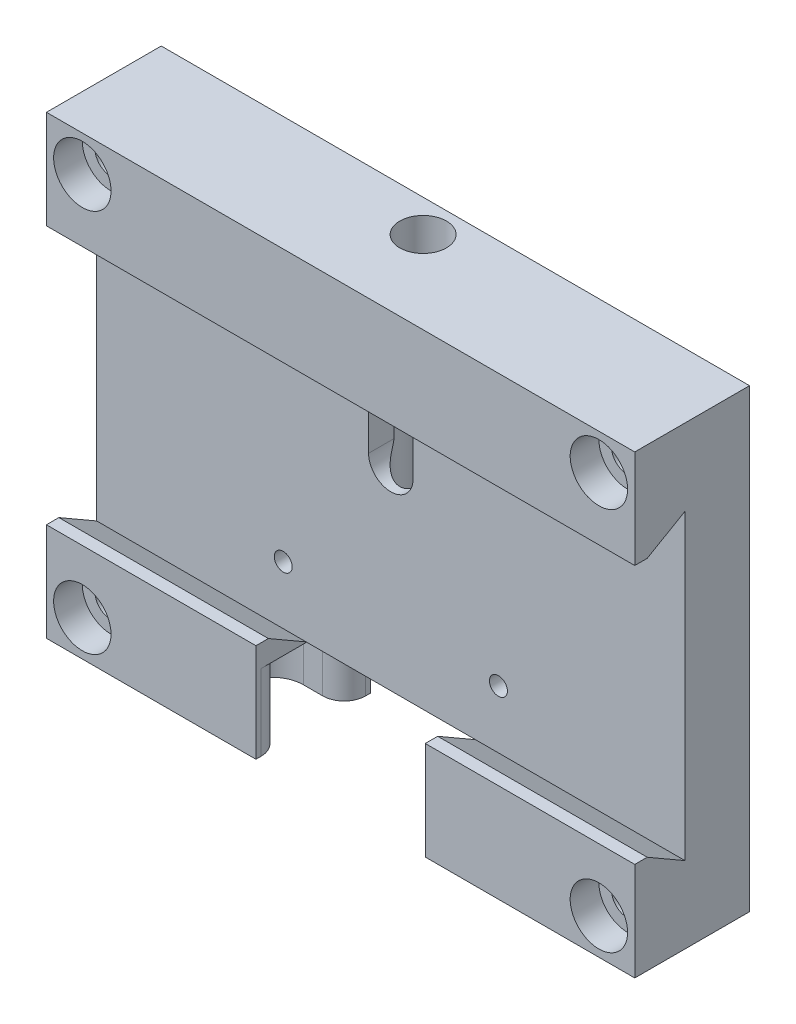
SolidWorks part; units mm, degrees
material "Сплав 2024"
ref_plane "Спереди" through (0, 0, 0) normal (0, 0, 1) x (1, 0, 0)
ref_plane "Сверху" through (0, 0, 0) normal (0, 1, 0) x (1, 0, 0)
ref_plane "Справа" through (0, 0, 0) normal (1, 0, 0) x (0, 0, -1)
sketch "Эскиз1" plane through (0, 0, 0) normal (0, 0, 1) x (1, 0, 0)
  line L1 (0, 0) -> (82, 0)
  line L2 (0, 0) -> (0, -63.5)
  line L3 (0, -63.5) -> (82, -63.5)
  line L4 (82, 0) -> (82, -63.5)
  dimension "D1" = 63.5
  dimension "D2" = 82
extrude "Бобышка-Вытянуть1" add sketch "Эскиз1" along normal blind 16
sketch "Эскиз2" plane through (0, 0, 0) normal (-1, 0, 0) x (0, 0, 1)
  line L0 (0, -31.75) -> (12.8711, -31.75) construction
  line L1 (0, 0) -> (0, -63.5) construction
  line L3 (16, 0) -> (16, -63.5) construction
  line L4 (9, -10.67) -> (16, -14.7115)
  line L5 (9, -10.67) -> (9, -52.83)
  line L6 (9, -52.83) -> (16, -48.7885)
  line L7 (16, -14.7115) -> (16, -48.7885)
  line L8 (9, -10.67) -> (16, -48.7885) construction
  line L9 (9, -52.83) -> (16, -14.7115) construction
  dimension "D1" = 42.16
  dimension "D2" = 60
  dimension "D3" = 60
  dimension "D4" = 7
extrude "Вырез-Вытянуть1" cut sketch "Эскиз2" against normal through all
ref_plane "Плоскость1" through (0, 0, 4) normal (0, 0, 1) x (1, 0, 0)
sketch "Эскиз11" plane through (0, 0, 0) normal (0, 0, -1) x (-1, 0, 0)
  line L0 (-82, -5) -> (0, -5) construction
  line L1 (-82, -63.5) -> (-82, 0) construction
  line L2 (0, 0) -> (0, -63.5) construction
  line L3 (-82, -58.5) -> (0, -58.5) construction
  line L4 (-82, 0) -> (0, 0) construction
  line L5 (0, -63.5) -> (-82, -63.5) construction
  line L8 (-82, -31.75) -> (0, -31.75) construction
  line L9 (-41, 0) -> (-41, -63.5) construction
  line L10 (-77, 0) -> (-77, -63.5) construction
  line L11 (-63.5, -11.75) -> (-18.5, -11.75) construction
  line L12 (-63.5, -11.75) -> (-63.5, -51.75) construction
  line L13 (-63.5, -51.75) -> (-18.5, -51.75) construction
  line L14 (-18.5, -11.75) -> (-18.5, -51.75) construction
  line L15 (-63.5, -11.75) -> (-18.5, -51.75) construction
  line L16 (-63.5, -51.75) -> (-18.5, -11.75) construction
  line L17 (-82, 0) -> (0, 0) construction
  line L18 (-82, -10.67) -> (-82, -52.83) construction
  line L19 (-5, 0) -> (-5, -63.5) construction
  line L20 (0, -10.67) -> (0, -52.83) construction
  line L21 (0, -63.5) -> (-82, -63.5) construction
  point P20 (-41, -31.75)
  dimension "D1" = 5
  dimension "D2" = 5
  dimension "D3" = 5
  dimension "D4" = 5
  dimension "D5" = 45
  dimension "D6" = 40
sketch "Эскиз15" plane through (0, 0, 16) normal (0, 0, 1) x (1, 0, 0)
  line L0 (41, 0) -> (41, -63.5) construction
  line L1 (82, 0) -> (0, 0) construction
  line L2 (0, -63.5) -> (82, -63.5) construction
  line L3 (82, -48.7885) -> (0, -48.7885) construction
  line L4 (29.2, -48.7885) -> (52.8, -48.7885)
  line L5 (29.2, -48.7885) -> (29.2, -63.5)
  line L6 (29.2, -63.5) -> (52.8, -63.5)
  line L7 (52.8, -48.7885) -> (52.8, -63.5)
  line L8 (29.2, -48.7885) -> (52.8, -63.5) construction
  line L9 (29.2, -63.5) -> (52.8, -48.7885) construction
  point P6 (41, -56.1443)
  dimension "D1" = 23.6
extrude "Вырез-Вытянуть4" cut sketch "Эскиз15" against normal up to surface (7 mm away) up to face at (41, -31.75, 9)
sketch "Эскиз16" plane through (0, 0, 9) normal (0, 0, 1) x (1, 0, 0)
  line L0 (41, 0) -> (41, -63.5) construction
  line L1 (29.2, -52.83) -> (52.8, -52.83)
  line L2 (29.2, -52.83) -> (29.2, -63.5)
  line L3 (29.2, -63.5) -> (52.8, -63.5)
  line L4 (52.8, -52.83) -> (52.8, -63.5)
  line L5 (29.2, -52.83) -> (52.8, -63.5) construction
  line L6 (29.2, -63.5) -> (52.8, -52.83) construction
  line L7 (29.2, -63.5) -> (52.8, -63.5) construction
  line L8 (82, -52.83) -> (52.8, -52.83) construction
  line L9 (52.8, -63.5) -> (52.8, -52.83) construction
  point P0 (41, -58.165)
extrude "Вырез-Вытянуть5" cut sketch "Эскиз16" against normal up to surface (9 mm away) up to face at (41, -31.75, 0)
sketch "Эскиз17" plane through (0, -52.83, 0) normal (0, -1, 0) x (1, 0, 0)
  line L0 (35.125, 5) -> (60.125, 5) construction
  line L3 (41, 9) -> (41, 0) construction
  line L4 (82, 9) -> (0, 9) construction
  line L5 (29.2, 0) -> (52.8, 0) construction
  circle A0 centre (33.5, 5) radius 2.5
  circle A1 centre (48.5, 5) radius 2.5
  dimension "D1" = 5
  dimension "D2" = 7.5
  dimension "D3" = 5
extrude "Вырез-Вытянуть6" cut sketch "Эскиз17" against normal blind 8
hole_wizard "Отверстие обработанное метчиком M4x0.72" positions "Эскиз19" profile "Эскиз18" tap size "M4x0.7" standard "Ansi Metric"
sketch "Эскиз19" plane through (0, -52.83, 0) normal (0, -1, 0) x (-1, 0, 0)
  line L0 (-41, -9) -> (-41, 0) construction
  line L1 (-35.125, -5) -> (-60.125, -5) construction
  point P0 (-41, -5)
sketch "Эскиз18" plane through (41, -52.83, 5) normal (1, 0, 0) x (0, 0, -1)
  line L0 (0, 0) -> (0, 10.9914)
  line L1 (0, 10.9914) -> (1.65, 10)
  line L2 (1.65, 10) -> (1.65, 0)
  line L5 (1.65, 0) -> (0, 0)
  line L10 (0, 10.9914) -> (-1.65, 10) construction
  line L11 (0, -6.35) -> (0, 107.95) construction
  dimension "Диаметр сверла" = 3.3
  dimension "Глубина сверла" = 10
  dimension "Угол заточки сверла" = 118
cosmetic thread "Отверстие резьбы9" parameters "D1"=8, "D2"=4
sketch "Эскиз25" plane through (0, 0, 9) normal (0, 0, 1) x (1, 0, 0)
  line L0 (41, 0) -> (41, -52.83) construction
  line L1 (82, 0) -> (0, 0) construction
  line L2 (52.8, -52.83) -> (29.2, -52.83) construction
  line L3 (41, -18.7115) -> (41, -25.7115) construction
  line L4 (44.1, -18.7115) -> (44.1, -25.7115)
  line L5 (37.9, -18.7115) -> (37.9, -25.7115)
  line L6 (82, -14.7115) -> (0, -14.7115) construction
  arc A0 (44.1, -18.7115) -> (37.9, -18.7115) centre (41, -18.7115) ccw
  arc A1 (37.9, -25.7115) -> (44.1, -25.7115) centre (41, -25.7115) ccw
  point P8 (41, -22.2115)
  dimension "D1" = 3.1
  dimension "D2" = 4
  dimension "D3" = 7
extrude "Вырез-Вытянуть7" cut sketch "Эскиз25" against normal blind 4
sketch "Эскиз26" plane through (0, 0, 0) normal (0, 1, 0) x (1, 0, 0)
  line L0 (0, -9) -> (82, -9) construction
  line L1 (0, -16) -> (0, 0) construction
  line L2 (82, -16) -> (82, 0) construction
  line L4 (82, 0) -> (0, 0) construction
  line L5 (41, 0) -> (41, -16) construction
  line L6 (82, -16) -> (0, -16) construction
  circle A0 centre (41, -4.5) radius 3.25
  dimension "D2" = 6.5
  dimension "D1" = 9
  dimension "D3" = 4.5
extrude "Вырез-Вытянуть8" cut sketch "Эскиз26" against normal blind 38
hole_wizard "Цековка для винта с внутренним шестигранником M41" positions "Эскиз29" profile "Эскиз28" counterbore size "M4" standard "Ansi Metric" end condition through all
sketch "Эскиз29" plane through (30.7592, 26.7934, 16) normal (0, 0, -1) x (-1, 0, 0)
  line L0 (-51.2408, -31.7934) -> (30.7592, -31.7934) construction
  line L1 (-46.2408, -26.7934) -> (-46.2408, -90.2934) construction
  line L2 (-51.2408, -85.2934) -> (30.7592, -85.2934) construction
  line L3 (25.7592, -26.7934) -> (25.7592, -90.2934) construction
  point P0 (-46.2408, -31.7934)
  point P6 (-46.2408, -85.2934)
  point P10 (25.7592, -85.2934)
  point P14 (25.7592, -31.7934)
sketch "Эскиз28" plane through (77, -5, 16) normal (1, 0, 0) x (0, -1, 0)
  line L0 (0, 0) -> (0, 16)
  line L1 (0, 16) -> (2.25, 16)
  line L3 (2.25, 16) -> (2.25, 4)
  line L4 (2.25, 4) -> (4, 4)
  line L5 (4, 4) -> (4, 0)
  line L7 (4, 0) -> (0, 0)
  line L11 (0, -6.35) -> (0, 107.95) construction
  dimension "Диаметр сквозного отверстия" = 4.5
  dimension "Глубина сквозного отверстия" = 16
  dimension "Диаметр цековки" = 8
  dimension "Глубина цековки" = 4
chamfer "Фаска2" distance 1 angle 90 3 edges at (67.4, -48.7885, 16) (14.6, -48.7885, 16) (41, -14.7115, 16)
sketch "Эскиз32" plane through (0, -63.5, 0) normal (0, -1, 0) x (1, 0, 0)
  line L0 (52.7, -0.2) -> (52.7, 3.7)
  line L1 (41, 9) -> (41, 0) construction
  line L2 (52.8, 9) -> (29.2, 9) construction
  line L3 (52.5, 0) -> (52.5, 3.9) construction
  line L4 (29.2, 8) -> (52.8, 8) construction
  line L5 (52.5, 3.9) -> (58.5, 3.9) construction
  line L6 (58.5, 12.1) -> (52.5, 12.1) construction
  line L7 (29.2, 0) -> (29.2, 16) construction
  line L8 (52.8, 0) -> (52.8, 9) construction
  line L9 (52.5, 12.1) -> (52.5, 16) construction
  line L10 (52.5, 16) -> (29.5, 16) construction
  line L11 (29.5, 16) -> (29.5, 12.1) construction
  line L12 (29.5, 12.1) -> (23.5, 12.1) construction
  line L13 (23.5, 3.9) -> (29.5, 3.9) construction
  line L14 (29.5, 3.9) -> (29.5, 0) construction
  line L15 (29.5, 0) -> (52.5, 0) construction
  line L16 (52.7, 3.7) -> (58.5, 3.7)
  line L17 (58.5, 12.3) -> (52.7, 12.3)
  line L18 (52.7, 12.3) -> (52.7, 16.2)
  line L19 (52.7, 16.2) -> (29.3, 16.2)
  line L20 (29.3, 16.2) -> (29.3, 12.3)
  line L21 (29.3, 12.3) -> (23.5, 12.3)
  line L22 (23.5, 3.7) -> (29.3, 3.7)
  line L23 (29.3, 3.7) -> (29.3, -0.2)
  line L24 (29.3, -0.2) -> (52.7, -0.2)
  arc A0 (58.5, 3.9) -> (58.5, 12.1) centre (58.5, 8) ccw construction
  arc A1 (23.5, 12.1) -> (23.5, 3.9) centre (23.5, 8) ccw construction
  arc A2 (58.5, 3.7) -> (58.5, 12.3) centre (58.5, 8) ccw
  arc A3 (23.5, 12.3) -> (23.5, 3.7) centre (23.5, 8) ccw
  point P7 (41, 16)
  point P20 (41, 0)
  dimension "D1" = 0.2
extrude "Вырез-Вытянуть12" cut sketch "Эскиз32" against normal blind 10.6
fillet "Скругление1" radius 3 4 edges at (52.8, -58.2, 12.3) (52.8, -58.2, 3.7) (29.2, -58.2, 3.7) (29.2, -58.2, 12.3)
sketch "Эскиз33" plane through (0, 0, 0) normal (0, 0, -1) x (-1, 0, 0)
  line L0 (0, -31.75) -> (-82, -31.75) construction
  line L1 (0, 0) -> (0, -63.5) construction
  line L2 (-82, -63.5) -> (-82, 0) construction
  line L3 (-41, 0) -> (-41, -52.83) construction
  line L4 (-82, 0) -> (0, 0) construction
  line L5 (-29.2, -52.83) -> (-52.8, -52.83) construction
  line L7 (-26, -44.75) -> (-56, -44.75) construction
  line L8 (-26, -44.75) -> (-26, -18.75) construction
  line L9 (-26, -18.75) -> (-56, -18.75) construction
  line L10 (-56, -44.75) -> (-56, -18.75) construction
  line L11 (-26, -44.75) -> (-56, -18.75) construction
  line L12 (-26, -18.75) -> (-56, -44.75) construction
  point P12 (-41, -31.75)
  dimension "D1" = 30
  dimension "D2" = 26
hole_wizard "Отверстие обработанное метчиком M3x0.51" positions "Эскиз35" profile "Эскиз34" tap size "M3x0.5" standard "Ansi Metric" end condition through all
sketch "Эскиз35" plane through (0, 0, 0) normal (0, 0, -1) x (-1, 0, 0)
  point P0 (-26, -44.75)
  point P3 (-26, -18.75)
  point P6 (-56, -18.75)
  point P9 (-56, -44.75)
sketch "Эскиз34" plane through (26, -44.75, 0) normal (1, 0, 0) x (0, 1, 0)
  line L0 (0, 0) -> (0, 16)
  line L1 (0, 16) -> (1.25, 16)
  line L2 (1.25, 16) -> (1.25, 0)
  line L5 (1.25, 0) -> (0, 0)
  line L11 (0, -6.35) -> (0, 107.95) construction
  dimension "Диаметр проходного сверла" = 2.5
  dimension "Глубина проходного сверла" = 16
cosmetic thread "Отверстие резьбы18" parameters "D2"=3
cosmetic thread "Отверстие резьбы19" parameters "D2"=3
cosmetic thread "Отверстие резьбы20" parameters "D2"=3
cosmetic thread "Отверстие резьбы21" parameters "D2"=3
